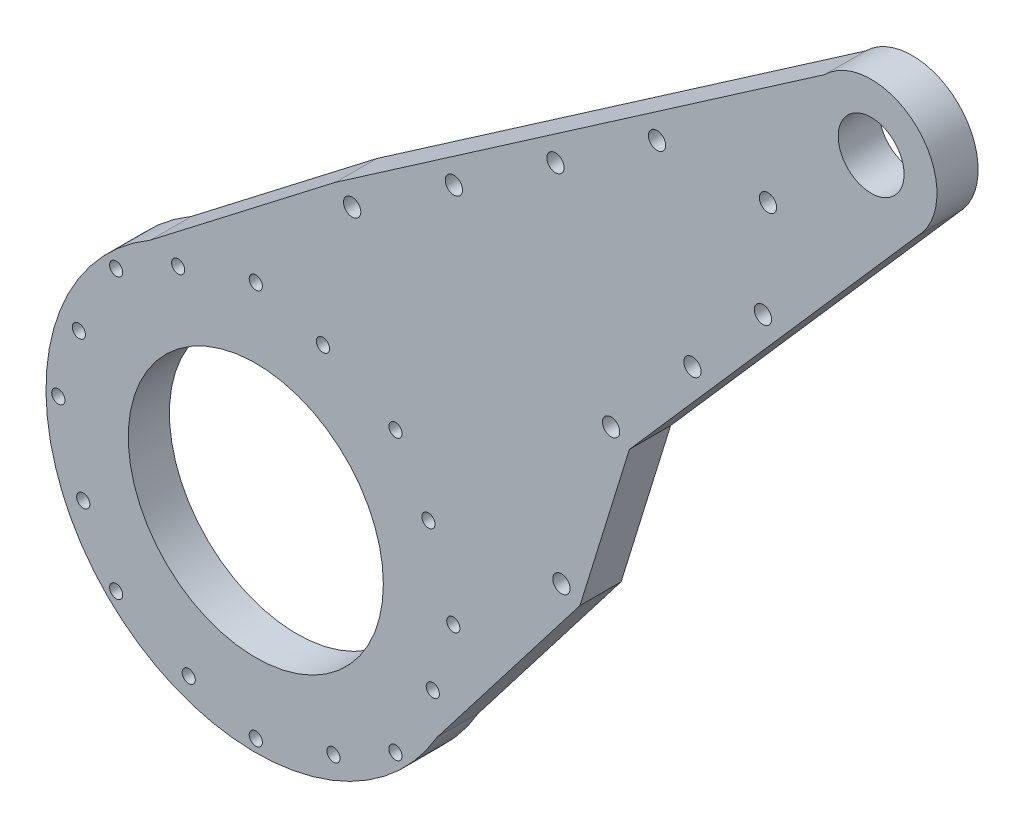
SolidWorks part; units mm, degrees
ref_plane "前视基准面" through (0, 0, 0) normal (0, 0, 1) x (1, 0, 0)
ref_plane "上视基准面" through (0, 0, 0) normal (0, 1, 0) x (1, 0, 0)
ref_plane "右视基准面" through (0, 0, 0) normal (1, 0, 0) x (0, 0, -1)
other "Configuration Table"
sketch "草图2" plane through (0, 0, 0) normal (0, 0, 1) x (1, 0, 0)
  line L0 (81.1412, 103.5011) -> (-37.71, 21.4194)
  line L1 (33.7077, 0.9133) -> (103.7686, 80.8737)
  line L2 (21.6869, -37.9775) -> (33.7077, 0.9133)
  line L3 (-13.0318, -83.0396) -> (21.6869, -37.9775)
  line L4 (-37.71, 21.4194) -> (-82.7722, -13.2993)
  circle A0 centre (17.1761, -35.6399) radius 2.1
  circle A1 centre (67.3786, 69.6902) radius 2.1
  circle A2 centre (40.415, 69.298) radius 2.1
  circle A3 centre (15.7298, 52.2498) radius 2.1
  circle A4 centre (-8.9554, 35.2016) radius 2.1
  circle A5 centre (29.2452, 3.4074) radius 2.1
  circle A6 centre (49.0156, 25.9713) radius 2.1
  circle A7 centre (66.15, 45.5267) radius 2.1
  circle A8 centre (-33.6808, 18.2119) radius 2.1
  circle A9 centre (-105.0982, -57.3657) radius 1.6
  circle A10 centre (-91.0393, -23.4246) radius 1.6
  circle A11 centre (-57.0982, -9.3657) radius 1.6
  circle A12 centre (-23.1571, -23.4246) radius 1.6
  circle A13 centre (-9.0982, -57.3657) radius 1.6
  circle A14 centre (-23.1571, -91.3068) radius 1.6
  circle A15 centre (-57.0982, -105.3657) radius 1.6
  circle A16 centre (-91.0393, -91.3068) radius 1.6
  circle A17 centre (92.4549, 92.1874) radius 8
  circle A18 centre (-100.1109, -41.0589) radius 1.6
  circle A19 centre (-73.405, -100.3784) radius 1.6
  circle A20 centre (-14.0856, -73.6725) radius 1.6
  circle A21 centre (-57.0982, -57.3657) radius 31
  circle A22 centre (-15.153, -38.4818) radius 1.6
  circle A23 centre (-38.2143, -99.3109) radius 1.6
  circle A24 centre (-99.0434, -76.2496) radius 1.6
  circle A25 centre (-75.9821, -15.4205) radius 1.6
  circle A26 centre (-40.7914, -14.3531) radius 1.6
  arc A27 (103.7686, 80.8737) -> (81.1412, 103.5011) centre (92.4549, 92.1874) ccw
  arc A28 (-82.7722, -13.2993) -> (-13.0318, -83.0396) centre (-57.0982, -57.3657) ccw
  dimension "D1" = 51
  dimension "D2" = 62
extrude "凸台-拉伸1" add sketch "草图2" along normal blind 10
